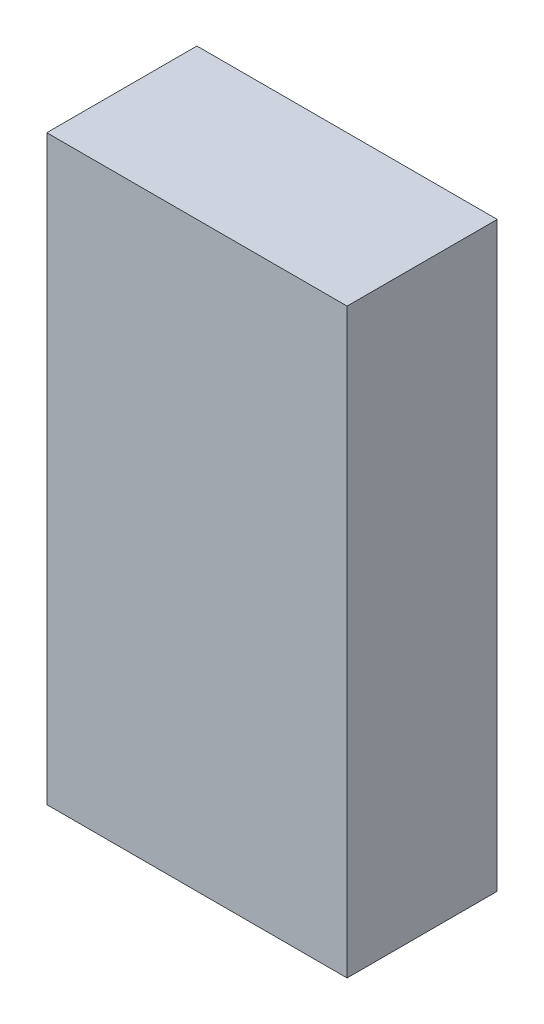
SolidWorks part; units mm, degrees
ref_plane "Front Plane" through (0, 0, 0) normal (0, 0, 1) x (1, 0, 0)
ref_plane "Top Plane" through (0, 0, 0) normal (0, 1, 0) x (1, 0, 0)
ref_plane "Right Plane" through (0, 0, 0) normal (1, 0, 0) x (0, 0, -1)
sketch "Sketch2" plane through (0, 0, 0) normal (0, 1, 0) x (1, 0, 0)
  line L1 (0, 0) -> (50.8, 0)
  line L2 (0, 0) -> (0, 25.4)
  line L3 (0, 25.4) -> (50.8, 25.4)
  line L4 (50.8, 0) -> (50.8, 25.4)
  dimension "D1" = 25.4
  dimension "D2" = 50.8
extrude "Boss-Extrude1" add sketch "Sketch2" along normal blind 98.425
sketch "Sketch4" plane through (0, 0, 0) normal (0, -1, 0) x (-1, 0, 0)
  line L0 (0, 0) -> (-50.8, 0) construction
  line L1 (-25.4, 0) -> (-25.4, 8.3981)
  circle A0 centre (-12.7, 12.7) radius 2.667
  circle A1 centre (-38.1, 12.7) radius 2.667
  dimension "D2" = 5.334
  dimension "D3" = 5.334
  dimension "D4" = 25.4
  dimension "D1" = 12.7
  dimension "D5" = 12.7
extrude "Cut-Extrude2" cut sketch "Sketch4" against normal blind 19.05 contours A0 | A1
sketch "Sketch5" plane through (0, 0, -25.4) normal (0, 0, -1) x (-1, 0, 0)
  line L0 (-50.8, 98.425) -> (-50.8, 0) construction
  line L1 (-50.8, 98.425) -> (0, 98.425) construction
  circle A0 centre (-25.4, 85.725) radius 4.826
  dimension "D3" = 9.652
  dimension "D1" = 25.4
  dimension "D2" = 12.7
extrude "Cut-Extrude3" cut sketch "Sketch5" against normal blind 12.7
